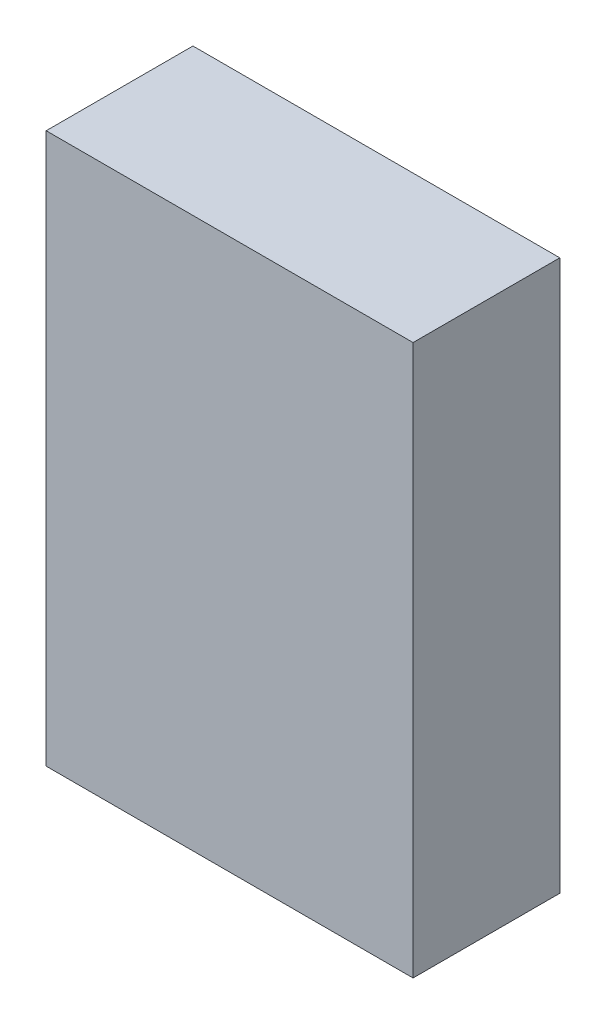
SolidWorks part; units mm, degrees
ref_plane "Front Plane" through (0, 0, 0) normal (0, 0, 1) x (1, 0, 0)
ref_plane "Top Plane" through (0, 0, 0) normal (0, 1, 0) x (1, 0, 0)
ref_plane "Right Plane" through (0, 0, 0) normal (1, 0, 0) x (0, 0, -1)
sketch "Sketch1" plane through (0, 0, 0) normal (0, 0, 1) x (1, 0, 0)
  line L1 (0, 0) -> (25.4, 0)
  line L2 (0, 0) -> (0, 38.1)
  line L3 (0, 38.1) -> (25.4, 38.1)
  line L4 (25.4, 0) -> (25.4, 38.1)
  dimension "D1" = 25.4
  dimension "D2" = 38.1
extrude "Boss-Extrude1" add sketch "Sketch1" along normal blind 10.16 contours L2 L3 L4 L1
sketch "Sketch2" plane through (0, 0, 0) normal (-1, 0, 0) x (0, 0, 1)
  line L0 (5.1307, 30.48) -> (5.1307, 7.62) construction
  line L1 (3.2257, 30.48) -> (3.2257, 7.62) construction
  line L2 (7.0357, 30.48) -> (7.0357, 7.62) construction
  line L3 (10.16, 38.1) -> (0, 38.1) construction
  line L4 (10.16, 0) -> (0, 0) construction
  line L5 (0, 0) -> (0, 38.1) construction
  circle A0 centre (5.1307, 30.48) radius 1.905
  circle A1 centre (5.1307, 7.62) radius 1.905
  point P4 (7.0357, 30.48)
  point P5 (3.2257, 30.48)
  point P6 (3.2257, 7.62)
  point P7 (7.0357, 7.62)
  point P14 (5.08, 38.1)
  point P17 (5.08, 0)
  dimension "D1" = 7.62
  dimension "D3" = 3.81
  dimension "D2" = 7.62
  dimension "D4" = 5.1307
extrude "Cut-Extrude1" cut sketch "Sketch2" against normal blind 10.16
